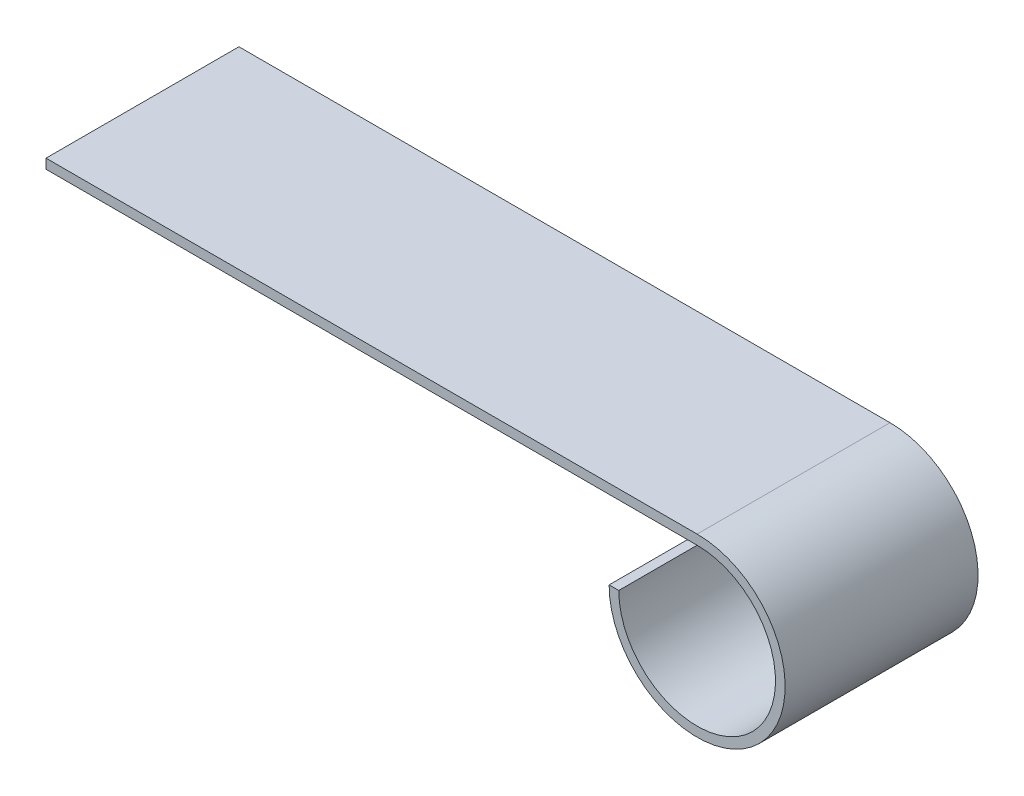
SolidWorks part; units mm, degrees
ref_plane "Plano frontal" through (0, 0, 0) normal (0, 0, 1) x (1, 0, 0)
ref_plane "Plano superior" through (0, 0, 0) normal (0, 1, 0) x (1, 0, 0)
ref_plane "Plano direito" through (0, 0, 0) normal (1, 0, 0) x (0, 0, -1)
sketch "Esboço1" plane through (0, 0, 0) normal (0, 0, 1) x (1, 0, 0)
  line L1 (20.4081, 0.8) -> (33.0775, 0.8)
  line L4 (20.4081, 1) -> (33.9081, 1)
  line L5 (33.0775, 0.8) -> (33.9081, 0.8)
  line L6 (32.2834, -0.8247) -> (32.0834, -0.8247)
  line L8 (20.4081, 1) -> (20.4081, 0.8)
  arc A2 (32.0834, -0.8247) -> (33.9081, 1) centre (33.9081, -0.8247) ccw
  arc A3 (32.2834, -0.8247) -> (33.9081, 0.8) centre (33.9081, -0.8247) ccw
  circle A4 centre (33.9081, -0.8247) radius 1.8247 construction
  circle A5 centre (33.9081, -0.8247) radius 1.6247 construction
  dimension "D1" = 0.2
extrude "Ressalto-extrusão1" add sketch "Esboço1" along normal blind 4
